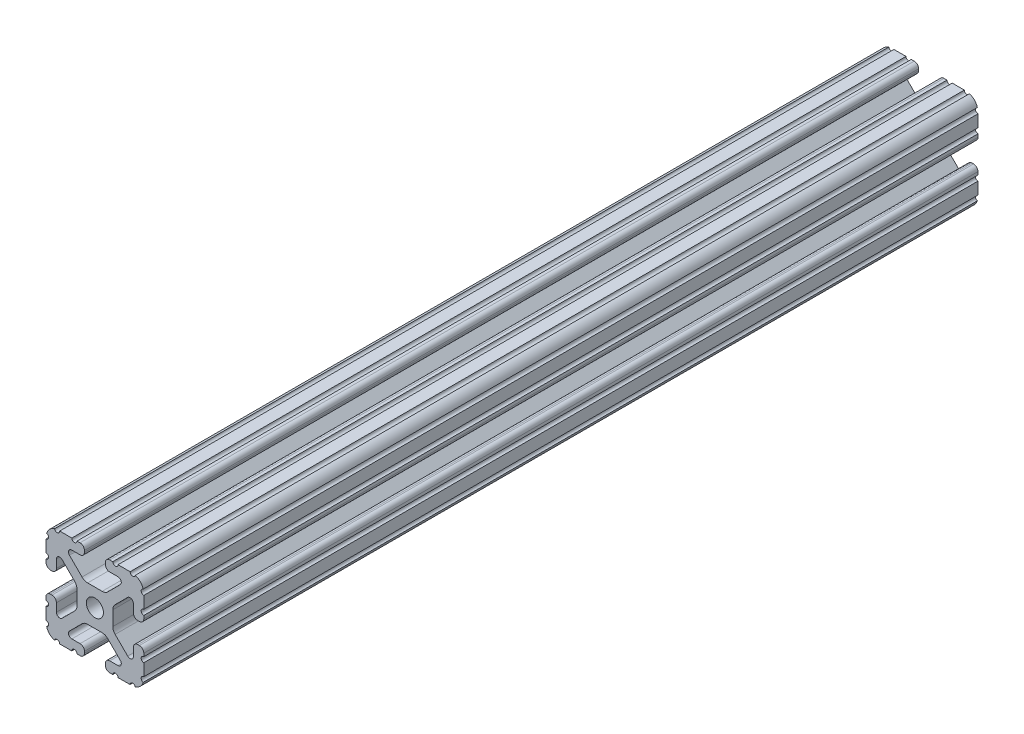
SolidWorks part; units mm, degrees
ref_plane "Front Plane" through (0, 0, 0) normal (0, 0, 1) x (1, 0, 0)
ref_plane "Top Plane" through (0, 0, 0) normal (0, 1, 0) x (1, 0, 0)
ref_plane "Right Plane" through (0, 0, 0) normal (1, 0, 0) x (0, 0, -1)
sketch "Sketch2" plane through (0, 0, 0) normal (0, 0, 1) x (1, 0, 0)
  line L0 (0, 19.05) -> (0, -19.05) construction
  line L1 (-19.05, 0) -> (19.05, 0) construction
  line L2 (4.064, -19.05) -> (19.05, -19.05)
  line L3 (19.05, -19.05) -> (19.05, -4.064)
  line L4 (4.064, -19.05) -> (4.064, -14.986)
  line L5 (4.064, -14.986) -> (12.1123, -14.986)
  line L6 (12.1123, -14.986) -> (4.1113, -6.985)
  line L7 (0, 0) -> (19.05, -19.05) construction
  line L8 (19.05, -4.064) -> (14.986, -4.064)
  line L9 (14.986, -4.064) -> (14.986, -12.1123)
  line L10 (14.986, -12.1123) -> (6.985, -4.1113)
  circle A0 centre (0, 0) radius 3.3274
  arc A1 (8.9963, -14.986) -> (9.909, -12.7826) centre (8.9963, -13.6953) ccw construction
  point P8 (0, -6.985)
  dimension "Center Hole Diameter" = 6.6548
  dimension "Rail Height" = 38.1
  dimension "Rail Width" = 38.1
  dimension "T-Slot Width" = 8.128
  dimension "Slot Inner Width" = 20.574
  dimension "Thickness" = 4.064
  dimension "Slot Depth" = 8.001
  dimension "D1" = 4.064
sketch "Sketch3" plane through (0, 0, 0) normal (1, 0, 0) x (0, 0, -1)
  line L0 (-162.515, -19.05) -> (162.515, -19.05) construction
  line L1 (-137.115, 0) -> (137.115, 0) construction
  dimension "Length" = 325.03
  dimension "D1" = 25.4
sketch "Sketch4" plane through (0, 0, 0) normal (0, 0, 1) x (1, 0, 0)
  line L0 (5.7912, -19.05) -> (14.3002, -19.05)
  line L1 (4.064, -19.05) -> (19.05, -19.05) construction
  line L2 (4.064, -19.05) -> (4.064, -14.986) construction
  line L3 (4.064, -14.986) -> (12.1123, -14.986) construction
  line L4 (4.064, -16.7132) -> (4.064, -17.3228)
  line L5 (5.7912, -14.986) -> (8.9963, -14.986)
  line L6 (0, -6.985) -> (2.833, -6.985)
  line L7 (12.1123, -14.986) -> (4.1113, -6.985) construction
  line L8 (5.0152, -7.8889) -> (9.909, -12.7826)
  line L9 (19.05, -19.05) -> (19.05, -4.064) construction
  line L10 (14.986, -12.1123) -> (6.985, -4.1113) construction
  line L11 (14.986, -4.064) -> (14.986, -12.1123) construction
  line L12 (14.986, -8.9963) -> (14.986, -5.7912)
  line L13 (19.05, -4.064) -> (14.986, -4.064) construction
  line L14 (16.7132, -4.064) -> (17.3228, -4.064)
  line L15 (19.05, -5.7912) -> (19.05, -14.3002)
  line L16 (12.7826, -9.909) -> (7.8889, -5.0152)
  line L17 (6.985, 0) -> (6.985, -2.833)
  line L18 (-19.05, 0) -> (19.05, 0) construction
  line L19 (0, -6.985) -> (0, -3.3274)
  line L20 (0, 19.05) -> (0, -19.05) construction
  line L21 (6.985, 0) -> (3.3274, 0)
  arc A0 (4.064, -17.3228) -> (5.7912, -19.05) centre (5.7912, -17.3228) ccw
  arc A2 (4.064, -16.7132) -> (5.7912, -14.986) centre (5.7912, -16.7132) cw
  arc A3 (8.9963, -14.986) -> (9.909, -12.7826) centre (8.9963, -13.6953) ccw
  arc A4 (2.833, -6.985) -> (5.0152, -7.8889) centre (2.833, -10.0711) cw
  arc A5 (14.3002, -19.05) -> (19.05, -14.3002) centre (14.3002, -14.3002) ccw
  arc A6 (12.7826, -9.909) -> (14.986, -8.9963) centre (13.6953, -8.9963) ccw
  arc A7 (14.986, -5.7912) -> (16.7132, -4.064) centre (16.7132, -5.7912) cw
  arc A8 (17.3228, -4.064) -> (19.05, -5.7912) centre (17.3228, -5.7912) cw
  arc A9 (7.8889, -5.0152) -> (6.985, -2.833) centre (10.0711, -2.833) cw
  circle A10 centre (0, 0) radius 3.3274 construction
  arc A11 (0, -3.3274) -> (3.3274, 0) centre (0, 0) ccw
  dimension "D1" = 4.7498
  dimension "D2" = 3.0861
  dimension "D3" = 1.7272
extrude "Boss-Extrude1" add sketch "Sketch4" along normal mid plane 325.03
sketch "Sketch5" plane through (0, 0, 0) normal (0, 0, 1) x (1, 0, 0)
  line L0 (4.064, -19.05) -> (19.05, -19.05) construction
  line L1 (5.7912, -14.986) -> (8.9963, -14.986) construction
  line L3 (0, 0) -> (19.05, -19.05) construction
  line L4 (8.9963, -14.986) -> (8.9963, -19.05) construction
  line L5 (12.1123, -14.986) -> (4.1113, -6.985) construction
  circle A0 centre (14.7395, -19.05) radius 1.016
  circle A1 centre (7.9803, -19.05) radius 1.016
  circle A2 centre (19.05, -14.7395) radius 1.016
  circle A3 centre (19.05, -7.9803) radius 1.016
  point P10 (7.3938, -14.986)
  point P12 (13.6953, -8.9963)
  dimension "D1" = 2.032
extrude "Cut-Extrude1" cut sketch "Sketch5" against normal through all both and the other way through all
mirror "Mirror1" about plane through (0, 0, 0) normal (1, 0, 0) of bodies 137 134
mirror "Mirror2" about plane through (0, 0, 0) normal (0, 1, 0) of bodies 135
equation "\"D1@Boss-Extrude1\"=\"Length@Sketch3\""
equation "\"D1@Sketch2\"=\"Thickness@Sketch2\""
equation "\"D2@Sketch4\"=\"Slot Inner Width@Sketch2\"*0.15"
equation "\"D1@Sketch4\"=\"D3@Sketch4\"*2.75"
equation "\"D3@Sketch4\"=\"Thickness@Sketch2\"*0.425"
equation "\"D1@Sketch5\"=\"Thickness@Sketch2\"*0.5"
